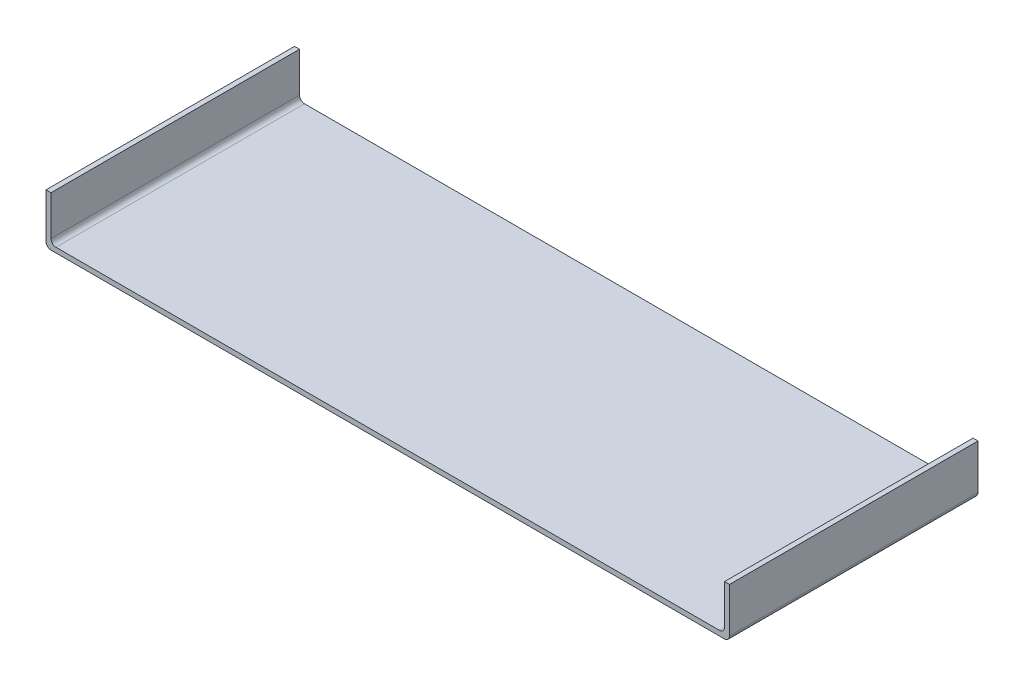
SolidWorks part; units mm, degrees
ref_plane "Front Plane" through (0, 0, 0) normal (0, 0, 1) x (1, 0, 0)
ref_plane "Top Plane" through (0, 0, 0) normal (0, 1, 0) x (1, 0, 0)
ref_plane "Right Plane" through (0, 0, 0) normal (1, 0, 0) x (0, 0, -1)
sketch "Sketch1" plane through (0, 0, 0) normal (0, 1, 0) x (1, 0, 0)
  line L1 (0, 0) -> (-275, 0)
  line L2 (0, 0) -> (0, 100)
  line L3 (0, 100) -> (-275, 100)
  line L4 (-275, 0) -> (-275, 100)
  dimension "D1" = 275
  dimension "D2" = 100
extrude "Boss-Extrude1" add sketch "Sketch1" along normal blind 20
shell "Shell2" thickness 2
fillet "Fillet1" radius 2 4 edges at (-275, 0, -50) (-2, 2, -50) (0, 0, -50) (-273, 2, -50)
